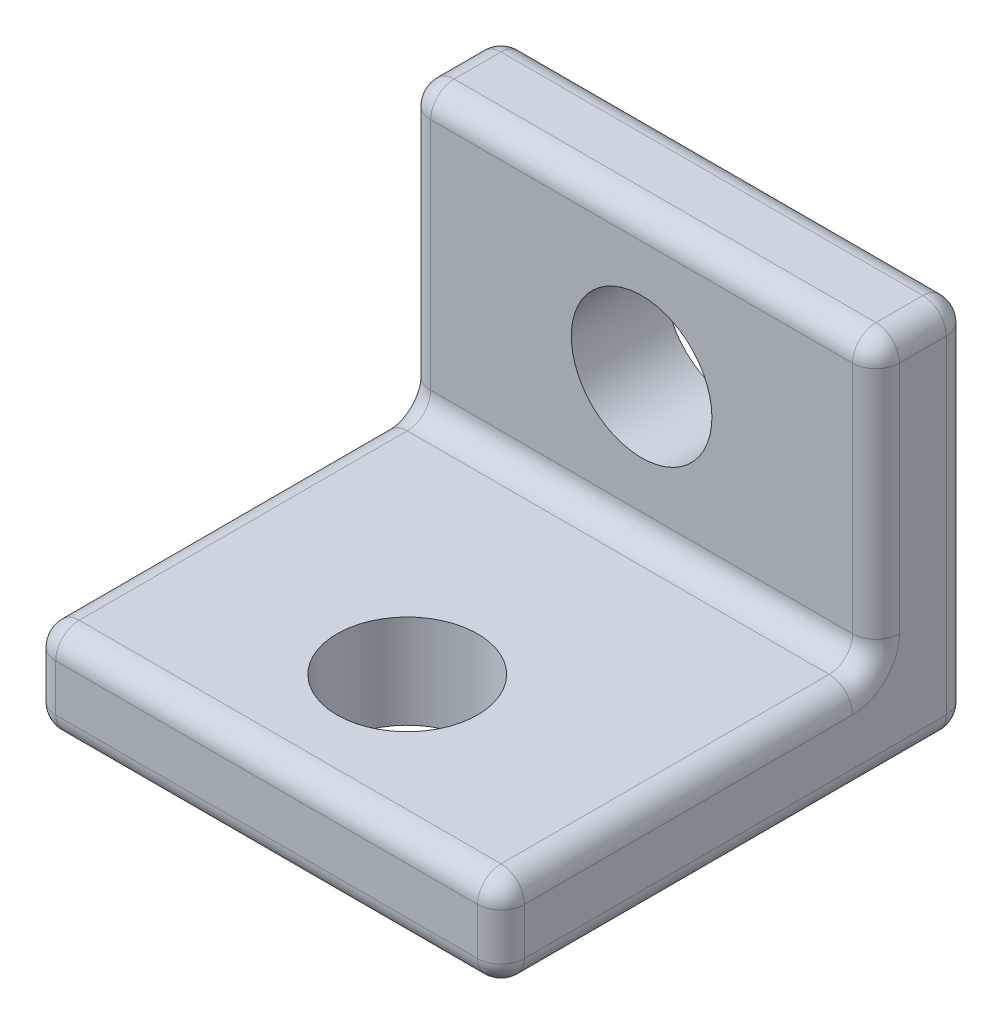
SolidWorks part; units mm, degrees
ref_plane "Front Plane" through (0, 0, 0) normal (0, 0, 1) x (1, 0, 0)
ref_plane "Top Plane" through (0, 0, 0) normal (0, 1, 0) x (1, 0, 0)
ref_plane "Right Plane" through (0, 0, 0) normal (1, 0, 0) x (0, 0, -1)
sketch "Sketch1" plane through (0, 0, 0) normal (0, 1, 0) x (1, 0, 0)
  line L1 (-5, 4) -> (5, 4)
  line L2 (-5, 4) -> (-5, -4)
  line L3 (-5, -4) -> (5, -4)
  line L4 (5, 4) -> (5, -4)
  line L5 (-5, 4) -> (5, -4) construction
  line L6 (-5, -4) -> (5, 4) construction
  point P0 (0, 0)
extrude "Boss-Extrude1" add sketch "Sketch1" along normal blind 2
sketch "Sketch2" plane through (0, 0, 0) normal (0, 1, 0) x (1, 0, 0)
  line L1 (-5, 6) -> (5, 6)
  line L2 (-5, 6) -> (-5, 4)
  line L3 (-5, 4) -> (5, 4)
  line L4 (5, 6) -> (5, 4)
  line L5 (-5, 6) -> (5, 4) construction
  line L6 (-5, 4) -> (5, 6) construction
  point P0 (0, 5)
extrude "Boss-Extrude2" add sketch "Sketch2" along normal blind 8
sketch "Sketch3" plane through (0, 2, 0) normal (0, 1, 0) x (1, 0, 0)
  line L0 (5, 4) -> (-5, 4) construction
  circle A0 centre (0, -1) radius 1.5
  dimension "D1" = 5
sketch "Sketch4" plane through (0, 0, -4) normal (0, 0, 1) x (1, 0, 0)
  line L0 (5, 2) -> (-5, 2) construction
  circle A0 centre (0, 5) radius 1.5
  dimension "D1" = 3
extrude "Cut-Extrude1" cut sketch "Sketch3" against normal through all
extrude "Cut-Extrude2" cut sketch "Sketch4" against normal through all contours A0
fillet "Fillet1" radius 0.5 18 edges at (0, 0, -6) (5, 0, -1) (0, 0, 4) (0, 2, 4) (-5, 0, -1) (-5, 8, -5) (-5, 4, -6) (0, 8, -6) (0, 8, -4) (5, 8, -5) (5, 4, -6) (5, 5, -4) (5, 2, 0) (5, 1, 4) (0, 2, -4) (-5, 5, -4) (-5, 2, 0) (-5, 1, 4)
